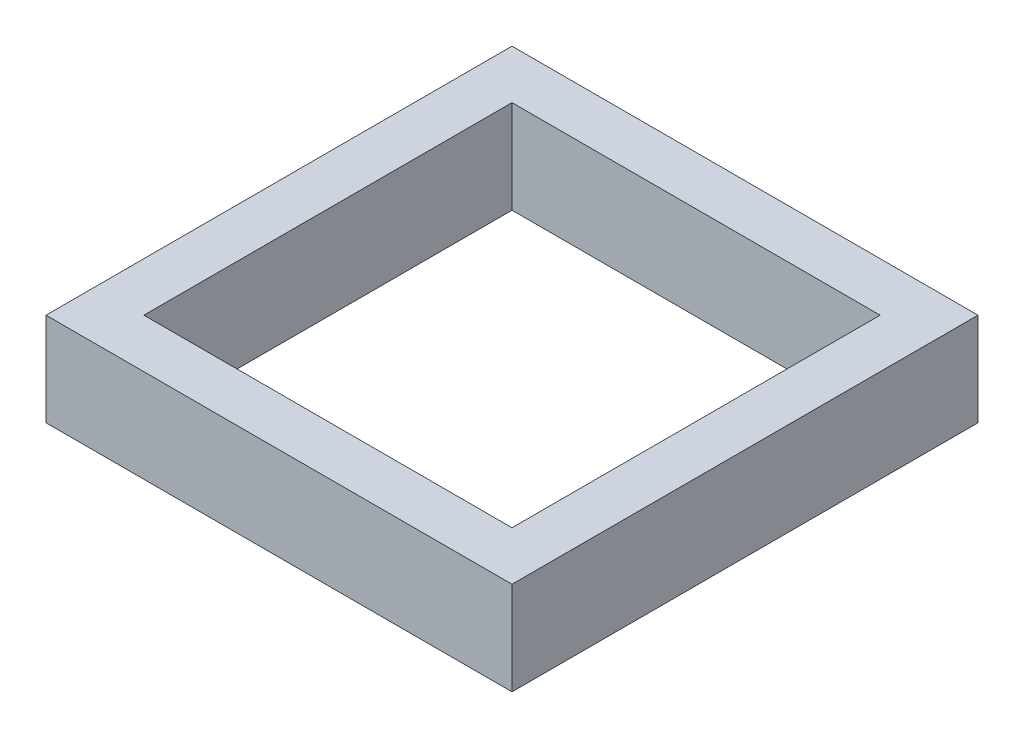
SolidWorks part; units mm, degrees
ref_plane "Alzado" through (0, 0, 0) normal (0, 0, 1) x (1, 0, 0)
ref_plane "Planta" through (0, 0, 0) normal (0, 1, 0) x (1, 0, 0)
ref_plane "Vista lateral" through (0, 0, 0) normal (1, 0, 0) x (0, 0, -1)
sketch "Croquis1" plane through (0, 0, 0) normal (0, 1, 0) x (1, 0, 0)
  line L1 (-100, 100) -> (100, 100)
  line L2 (-100, 100) -> (-100, -100)
  line L3 (-100, -100) -> (100, -100)
  line L4 (100, 100) -> (100, -100)
  line L5 (-100, 100) -> (100, -100) construction
  line L6 (-100, -100) -> (100, 100) construction
  line L7 (-79, 79) -> (79, 79)
  line L8 (-79, 79) -> (-79, -79)
  line L9 (-79, -79) -> (79, -79)
  line L10 (79, 79) -> (79, -79)
  line L11 (-79, 79) -> (79, -79) construction
  line L12 (-79, -79) -> (79, 79) construction
  point P0 (0, 0)
  point P5 (0, 0)
  dimension "D1" = 158
  dimension "D2" = 200
extrude "Saliente-Extruir1" add sketch "Croquis1" along normal blind 40
